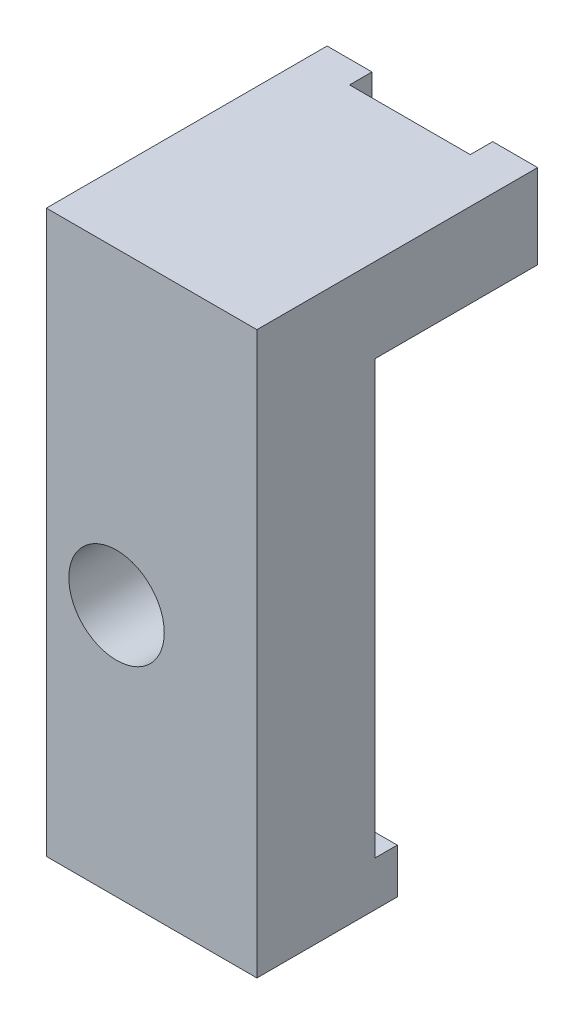
SolidWorks part; units mm, degrees
ref_plane "Front Plane" through (0, 0, 0) normal (0, 0, 1) x (1, 0, 0)
ref_plane "Top Plane" through (0, 0, 0) normal (0, 1, 0) x (1, 0, 0)
ref_plane "Right Plane" through (0, 0, 0) normal (1, 0, 0) x (0, 0, -1)
sketch "Sketch1" plane through (0, 0, 0) normal (0, 0, 1) x (1, 0, 0)
  line L1 (-4.7625, 12.7) -> (4.7625, 12.7)
  line L2 (-4.7625, 12.7) -> (-4.7625, -12.7)
  line L3 (-4.7625, -12.7) -> (4.7625, -12.7)
  line L4 (4.7625, 12.7) -> (4.7625, -12.7)
  line L5 (-4.7625, 12.7) -> (4.7625, -12.7) construction
  line L6 (-4.7625, -12.7) -> (4.7625, 12.7) construction
  point P0 (0, 0)
  dimension "D1" = 25.4
  dimension "D2" = 9.525
extrude "Boss-Extrude1" add sketch "Sketch1" along normal mid plane 12.7
sketch "Sketch2" plane through (4.7625, 0, 0) normal (1, 0, 0) x (0, 0, -1)
  line L0 (-6.35, -12.7) -> (-6.35, 12.7) construction
  line L1 (6.35, -12.7) -> (0, -12.7)
  line L2 (6.35, -12.7) -> (6.35, 8.89)
  line L3 (6.35, 8.89) -> (0, 8.89)
  line L4 (0, -12.7) -> (0, 8.89)
  line L5 (-6.35, 12.7) -> (6.35, 12.7) construction
  dimension "D1" = 6.35
  dimension "D2" = 3.81
extrude "Cut-Extrude1" cut sketch "Sketch2" against normal up to next
sketch "Sketch3" plane through (0, 0, 6.35) normal (0, 0, 1) x (1, 0, 0)
  line L0 (-4.7625, -12.7) -> (4.7625, -12.7) construction
  line L1 (-4.7625, 12.7) -> (-4.7625, -12.7) construction
  circle A0 centre (-1.5875, -1.27) radius 2.159
  dimension "D1" = 11.43
  dimension "D2" = 3.175
extrude "Cut-Extrude2" cut sketch "Sketch3" against normal up to next
sketch "Sketch4" plane through (0, 12.7, 0) normal (0, 1, 0) x (1, 0, 0)
  line L0 (4.7625, 6.35) -> (-4.7625, 6.35) construction
  line L1 (2.7305, 6.35) -> (-2.7305, 6.35)
  line L2 (2.7305, 6.35) -> (2.7305, 5.334)
  line L3 (2.7305, 5.334) -> (-2.7305, 5.334)
  line L4 (-2.7305, 6.35) -> (-2.7305, 5.334)
  line L5 (-4.7625, -6.35) -> (-4.7625, 6.35) construction
  line L6 (4.7625, -6.35) -> (4.7625, 6.35) construction
  dimension "D1" = 2.032
  dimension "D2" = 2.032
  dimension "D3" = 1.016
extrude "Cut-Extrude3" cut sketch "Sketch4" against normal up to next
sketch "Sketch5" plane through (4.7625, 0, 0) normal (1, 0, 0) x (0, 0, -1)
  line L0 (0, 8.89) -> (0, -12.7) construction
  line L1 (0, -10.668) -> (-1.016, -10.668)
  line L2 (0, -10.668) -> (0, 8.89)
  line L3 (0, 8.89) -> (-1.016, 8.89)
  line L4 (-1.016, -10.668) -> (-1.016, 8.89)
  line L5 (-6.35, -12.7) -> (0, -12.7) construction
  line L6 (6.35, 8.89) -> (0, 8.89) construction
  dimension "D1" = 2.032
  dimension "D2" = 1.016
extrude "Cut-Extrude4" cut sketch "Sketch5" against normal through all
